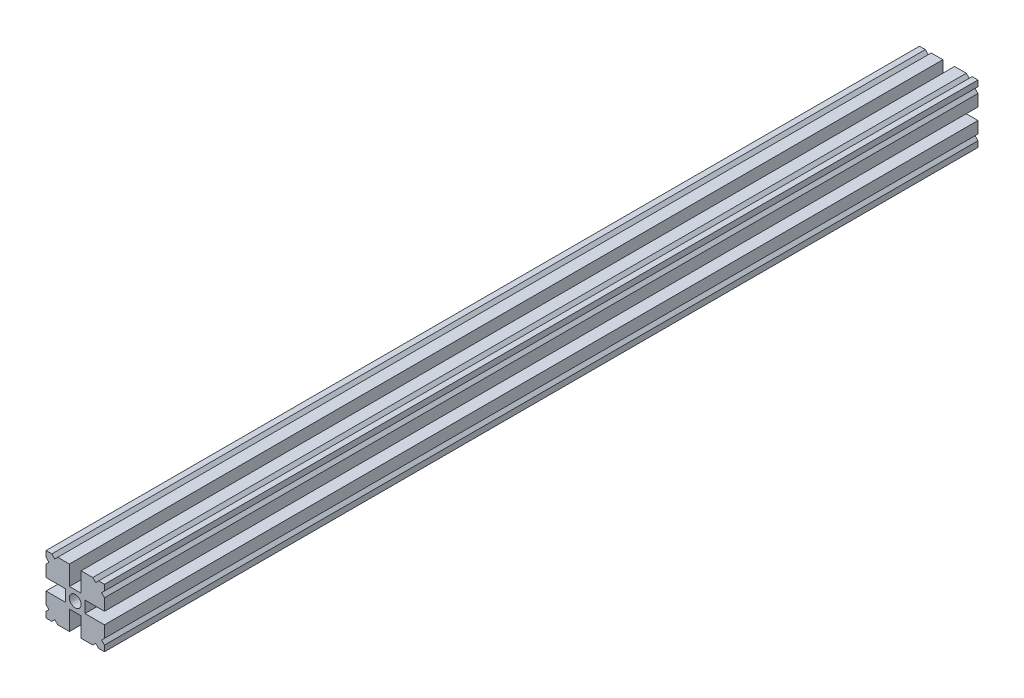
SolidWorks part; units mm, degrees
ref_plane "Front Plane" through (0, 0, 0) normal (0, 0, 1) x (1, 0, 0)
ref_plane "Top Plane" through (0, 0, 0) normal (0, 1, 0) x (1, 0, 0)
ref_plane "Right Plane" through (0, 0, 0) normal (1, 0, 0) x (0, 0, -1)
sketch "Sketch1" plane through (0, 0, 0) normal (0, 0, 1) x (1, 0, 0)
  line L0 (-1.5, 7.5) -> (1.5, 7.5) construction
  line L1 (-7.5, 7.5) -> (7.5, 7.5) construction
  line L2 (-7.5, 7.5) -> (-7.5, -7.5) construction
  line L3 (-7.5, -7.5) -> (7.5, -7.5) construction
  line L4 (7.5, 7.5) -> (7.5, -7.5) construction
  line L5 (-7.5, 7.5) -> (7.5, -7.5) construction
  line L6 (-7.5, -7.5) -> (7.5, 7.5) construction
  line L7 (-7.5, 7.5) -> (-6, 7.5)
  line L8 (7.5, 7.5) -> (6, 7.5)
  line L9 (-6, 7.5) -> (-5.25, 6.75)
  line L10 (-5.25, 6.75) -> (-4.5, 7.5)
  line L11 (-4.5, 7.5) -> (-1.5, 7.5)
  line L12 (-1.5, 7.5) -> (-1.5, 2.5)
  line L13 (-1.5, 2.5) -> (1.5, 2.5)
  line L14 (1.5, 2.5) -> (1.5, 7.5)
  line L15 (1.5, 7.5) -> (4.5, 7.5)
  line L16 (4.5, 7.5) -> (5.25, 6.75)
  line L17 (5.25, 6.75) -> (6, 7.5)
  line L18 (7.5, 7.5) -> (7.5, 6)
  line L19 (7.5, 6) -> (6.75, 5.25)
  line L20 (6.75, 5.25) -> (7.5, 4.5)
  line L21 (7.5, 4.5) -> (7.5, 1.5)
  line L22 (7.5, 1.5) -> (2.5, 1.5)
  line L23 (2.5, 1.5) -> (2.5, -1.5)
  line L24 (2.5, -1.5) -> (7.5, -1.5)
  line L25 (7.5, -1.5) -> (7.5, -4.5)
  line L26 (6.75, -5.25) -> (7.5, -6)
  line L27 (7.5, -4.5) -> (6.75, -5.25)
  line L28 (7.5, -7.5) -> (7.5, -6)
  line L29 (7.5, -7.5) -> (6, -7.5)
  line L30 (6, -7.5) -> (5.25, -6.75)
  line L31 (5.25, -6.75) -> (4.5, -7.5)
  line L32 (4.5, -7.5) -> (1.5, -7.5)
  line L33 (1.5, -7.5) -> (1.5, -2.5)
  line L34 (1.5, -2.5) -> (-1.5, -2.5)
  line L35 (-1.5, -2.5) -> (-1.5, -7.5)
  line L36 (-1.5, -7.5) -> (-4.5, -7.5)
  line L37 (-5.25, -6.75) -> (-6, -7.5)
  line L38 (-4.5, -7.5) -> (-5.25, -6.75)
  line L39 (-7.5, -7.5) -> (-6, -7.5)
  line L40 (-7.5, -7.5) -> (-7.5, -6)
  line L41 (-7.5, -6) -> (-6.75, -5.25)
  line L42 (-6.75, -5.25) -> (-7.5, -4.5)
  line L43 (-7.5, -4.5) -> (-7.5, -1.5)
  line L44 (-7.5, -1.5) -> (-2.5, -1.5)
  line L45 (-2.5, -1.5) -> (-2.5, 1.5)
  line L46 (-2.5, 1.5) -> (-7.5, 1.5)
  line L47 (-7.5, 1.5) -> (-7.5, 4.5)
  line L48 (-6.75, 5.25) -> (-7.5, 6)
  line L49 (-7.5, 4.5) -> (-6.75, 5.25)
  line L50 (-7.5, 7.5) -> (-7.5, 6)
  circle A0 centre (0, 0) radius 1.5
  point P0 (0, 0)
  point P8 (0, 7.5)
  point P56 (0, 0)
  dimension "D8" = 3
  dimension "D1" = 15
  dimension "D2" = 3
  dimension "D3" = 1.5
  dimension "D4" = 5
  dimension "D5" = 1.5
  dimension "D6" = 3
  dimension "D7" = 4
extrude "Boss-Extrude1" add sketch "Sketch1" along normal blind 224
ref_plane "Plane1" through (0, 0, 112) normal (0, 0, 1) x (1, 0, 0)
